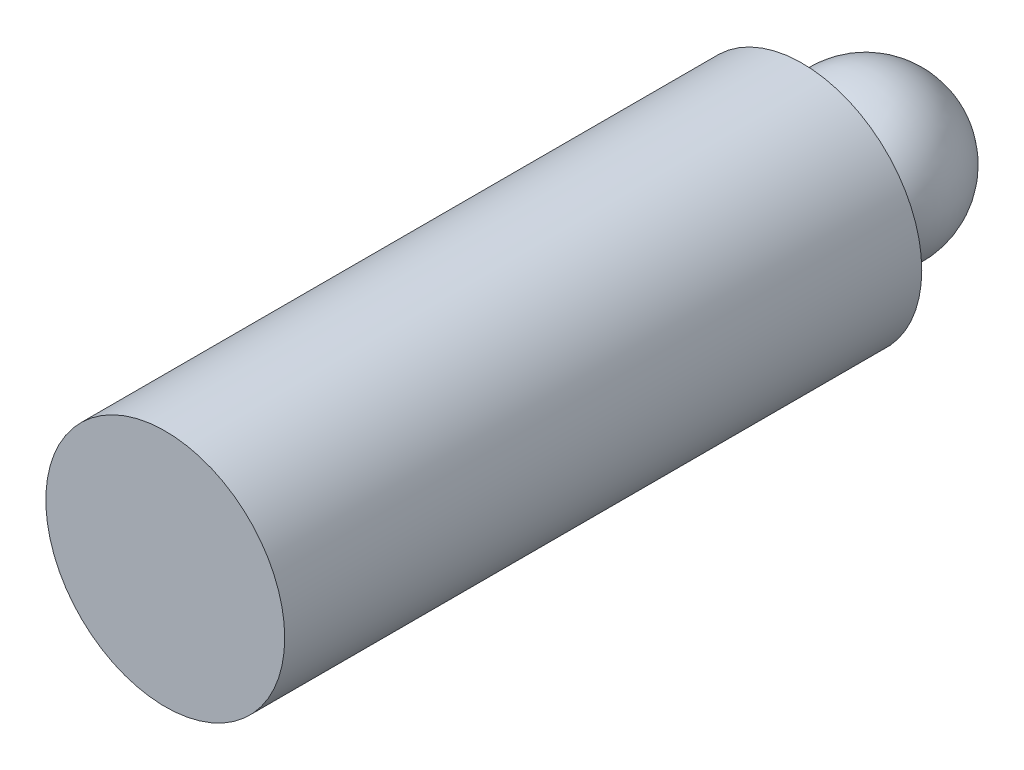
SolidWorks part; units mm, degrees
ref_plane "前视基准面" through (0, 0, 0) normal (0, 0, 1) x (1, 0, 0)
ref_plane "上视基准面" through (0, 0, 0) normal (0, 1, 0) x (1, 0, 0)
ref_plane "右视基准面" through (0, 0, 0) normal (1, 0, 0) x (0, 0, -1)
other "Configuration Table"
sketch "草图1" plane through (0, 0, 0) normal (0, 0, 1) x (1, 0, 0)
  circle A0 centre (0, 0) radius 15
  dimension "D1" = 30
extrude "凸台-拉伸1" add sketch "草图1" along normal blind 80
sketch "草图3" plane through (0, 0, 0) normal (0, 1, 0) x (1, 0, 0)
  line L0 (0, 17.9415) -> (0, -2.0585)
  arc A0 (0, 17.9415) -> (0, -2.0585) centre (0, 7.9415) ccw
  point P1 (-4.6605, 40.2976)
  point P5 (0, 20.1477)
  point P6 (0, 7.9415)
  dimension "D1" = 20
revolve "旋转1" add sketch "草图3" angle 360 about L0
